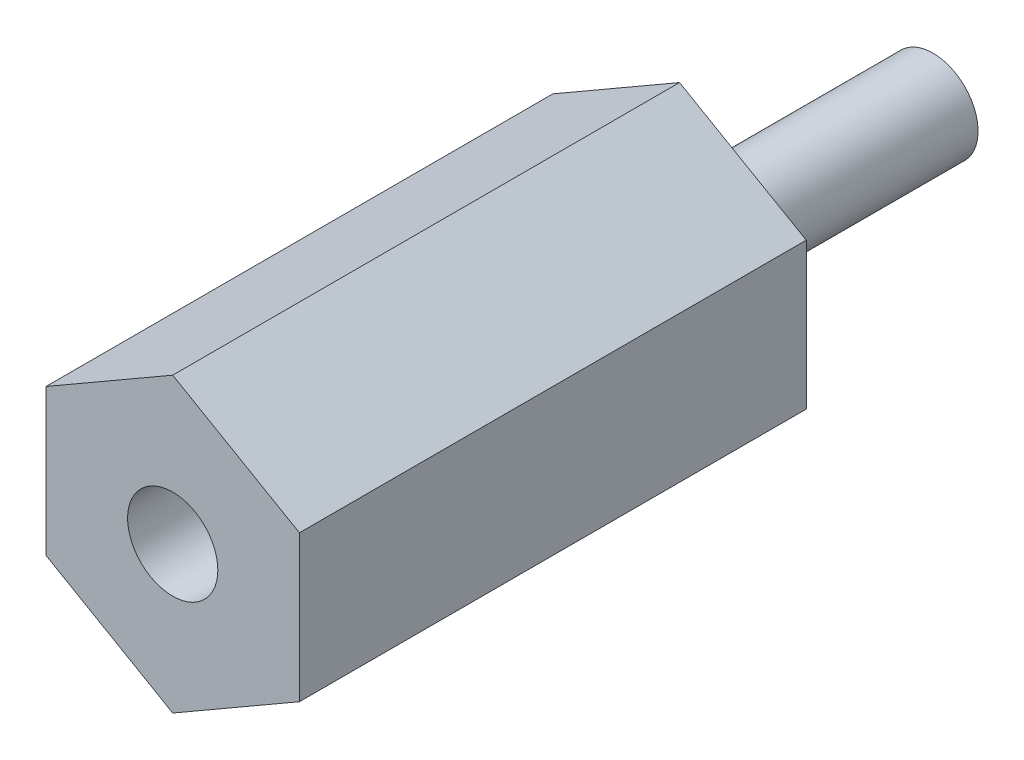
SolidWorks part; units mm, degrees
material "6061-T6 (SS)"
ref_plane "Front Plane" through (0, 0, 0) normal (0, 0, 1) x (1, 0, 0)
ref_plane "Top Plane" through (0, 0, 0) normal (0, 1, 0) x (1, 0, 0)
ref_plane "Right Plane" through (0, 0, 0) normal (1, 0, 0) x (0, 0, -1)
sketch "Sketch1" plane through (0, 0, 0) normal (0, 0, 1) x (1, 0, 0)
  line L1 (0, 3.6662) -> (-3.175, 1.8331)
  line L2 (-3.175, 1.8331) -> (-3.175, -1.8331)
  line L3 (-3.175, -1.8331) -> (0, -3.6662)
  line L4 (0, -3.6662) -> (3.175, -1.8331)
  line L5 (3.175, -1.8331) -> (3.175, 1.8331)
  line L6 (3.175, 1.8331) -> (0, 3.6662)
  circle A0 centre (0, 0) radius 3.175 construction
  dimension "D1" = 6.35
extrude "Boss-Extrude1" add sketch "Sketch1" along normal blind 12.7
hole_wizard "Tap Drill for #4-40 Tap1" positions "Sketch3" profile "Sketch2" hole size "#4-40" standard "ANSI Inch"
sketch "Sketch3" plane through (0, 0, 12.7) normal (0, 0, 1) x (1, 0, 0)
  point P0 (0, 0)
sketch "Sketch2" plane through (0, 0, 12.7) normal (1, 0, 0) x (0, -1, 0)
  line L0 (0, 0) -> (0, 13.3792)
  line L1 (0, 13.3792) -> (1.1303, 12.7)
  line L2 (1.1303, 12.7) -> (1.1303, 0)
  line L5 (1.1303, 0) -> (0, 0)
  line L10 (0, 13.3792) -> (-1.1303, 12.7) construction
  line L11 (0, -6.35) -> (0, 107.95) construction
  dimension "Hole Dia." = 2.2606
  dimension "Hole Depth" = 12.7
  dimension "Drill Angle" = 118
sketch "Sketch5" plane through (0, 0, 0) normal (0, 0, -1) x (-1, 0, 0)
  circle A0 centre (0, 0) radius 1.1303
  circle A1 centre (0, 0) radius 1.1303 construction
extrude "Boss-Extrude2" add sketch "Sketch5" along normal blind 6.35
